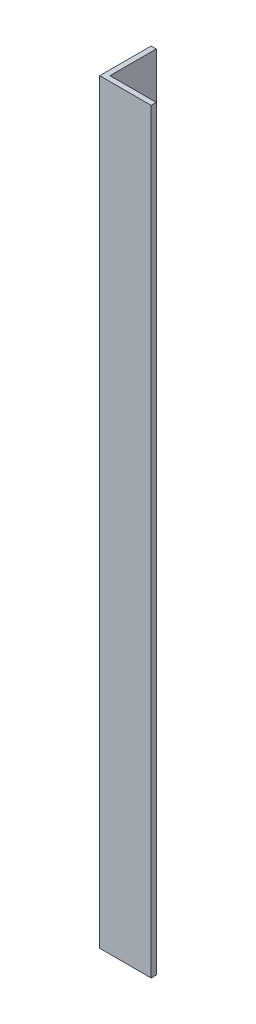
SolidWorks part; units mm, degrees
material "1060 Alloy"
ref_plane "Front Plane" through (0, 0, 0) normal (0, 0, 1) x (1, 0, 0)
ref_plane "Top Plane" through (0, 0, 0) normal (0, 1, 0) x (1, 0, 0)
ref_plane "Right Plane" through (0, 0, 0) normal (1, 0, 0) x (0, 0, -1)
sketch "Sketch1" plane through (0, 0, 0) normal (0, 1, 0) x (1, 0, 0)
  line L1 (0, 0) -> (20, 0)
  line L2 (0, 0) -> (0, 20)
  line L3 (0, 20) -> (2, 20)
  line L4 (20, 0) -> (20, 2)
  line L7 (20, 2) -> (2, 2)
  line L8 (2, 20) -> (2, 2)
  dimension "D1" = 20
  dimension "D2" = 20
  dimension "D3" = 2
  dimension "D4" = 2
extrude "Boss-Extrude1" add sketch "Sketch1" along normal blind 294
